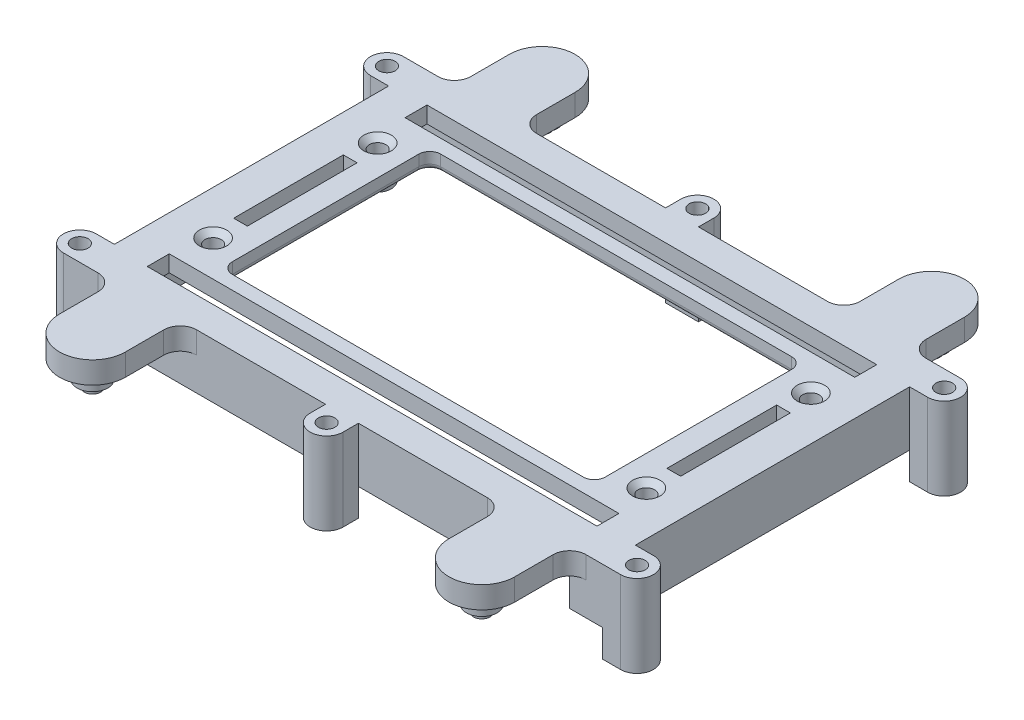
SolidWorks part; units mm, degrees
ref_plane "前视基准面" through (0, 0, 0) normal (0, 0, 1) x (1, 0, 0)
ref_plane "上视基准面" through (0, 0, 0) normal (0, 1, 0) x (1, 0, 0)
ref_plane "右视基准面" through (0, 0, 0) normal (1, 0, 0) x (0, 0, -1)
other "Configuration Table"
sketch "草图1" plane through (0, 0, 0) normal (0, 1, 0) x (1, 0, 0)
  line L0 (0, 35.4779) -> (0, -35.3561) construction
  line L1 (-47.5, 31) -> (-41.5, 31)
  line L2 (-47.5, 25) -> (-47.5, -25)
  line L3 (-47.5, -31) -> (-41.5, -31)
  line L4 (47.5, 25) -> (47.5, -25)
  line L5 (-47.5, 31) -> (47.5, -31) construction
  line L6 (-47.5, -31) -> (47.5, 31) construction
  line L9 (-41.5, 31) -> (-41.5, 41)
  line L11 (-29.5, 31) -> (-29.5, 41)
  line L12 (29.5, 31) -> (29.5, 41)
  line L14 (41.5, 31) -> (41.5, 41)
  line L15 (-78.7463, 0) -> (58.6748, 0) construction
  line L16 (41.5, -31) -> (41.5, -41)
  line L18 (29.5, -31) -> (29.5, -41)
  line L21 (-29.5, -31) -> (-29.5, -41)
  line L23 (-41.5, -31) -> (-41.5, -41)
  line L24 (-29.5, 31) -> (-3, 31)
  line L25 (41.5, 31) -> (47.5, 31)
  line L26 (41.5, -31) -> (47.5, -31)
  line L27 (-29.5, -31) -> (-3, -31)
  line L28 (47.5, 31) -> (50.8, 31)
  line L29 (-47.5, 31) -> (-50.8, 31)
  line L31 (-47.5, 25) -> (-50.8, 25)
  line L33 (47.5, 25) -> (50.8, 25)
  line L36 (47.5, -25) -> (50.8, -25)
  line L37 (47.5, -31) -> (50.8, -31)
  line L38 (-47.5, -31) -> (-50.8, -31)
  line L39 (-47.5, -25) -> (-50.8, -25)
  line L41 (-3, -33.8) -> (-3, -31)
  line L43 (-3, 33.8) -> (-3, 31)
  line L45 (3, 33.8) -> (3, 31)
  line L47 (3, -33.8) -> (3, -31)
  line L48 (3, 31) -> (29.5, 31)
  line L49 (3, -31) -> (29.5, -31)
  arc A0 (-41.5, 41) -> (-29.5, 41) centre (-35.5, 41) cw
  arc A1 (-41.5, -41) -> (-29.5, -41) centre (-35.5, -41) ccw
  arc A2 (41.5, -41) -> (29.5, -41) centre (35.5, -41) cw
  arc A3 (41.5, 41) -> (29.5, 41) centre (35.5, 41) ccw
  arc A4 (-50.8, 31) -> (-50.8, 25) centre (-50.8, 28) ccw
  circle A5 centre (-50.8, 28) radius 1.5
  circle A6 centre (50.8, 28) radius 1.5
  arc A7 (50.8, 31) -> (50.8, 25) centre (50.8, 28) cw
  circle A8 centre (50.8, -28) radius 1.5
  arc A9 (50.8, -31) -> (50.8, -25) centre (50.8, -28) ccw
  circle A10 centre (-50.8, -28) radius 1.5
  arc A11 (-50.8, -31) -> (-50.8, -25) centre (-50.8, -28) cw
  arc A12 (-3, 33.8) -> (3, 33.8) centre (0, 33.8) cw
  circle A13 centre (0, 33.8) radius 1.5
  circle A14 centre (0, -33.8) radius 1.5
  arc A15 (-3, -33.8) -> (3, -33.8) centre (0, -33.8) ccw
  point P0 (0, 0)
  dimension "D8" = 2.8
  dimension "D1" = 95
  dimension "D2" = 62
  dimension "D3" = 83
  dimension "D4" = 12
  dimension "D5" = 10
  dimension "D6" = 3.3
  dimension "D7" = 6
  dimension "D9" = 6
extrude "凸台-拉伸1" add sketch "草图1" against normal blind 15
sketch "草图2" plane through (0, -15, 0) normal (0, -1, 0) x (1, 0, 0)
  line L0 (-63.1336, 0) -> (63.5579, 0) construction
  line L1 (-57.0239, 31) -> (-3, 31)
  line L2 (-57.0239, 31) -> (-57.0239, 48.5806)
  line L3 (-57.0239, 48.5806) -> (57.0239, 48.5806)
  line L4 (57.0239, 31) -> (57.0239, 48.5806)
  line L5 (0, 56.9992) -> (0, -44.1169) construction
  line L6 (3, 33.8) -> (3, 31) construction
  line L7 (-3, 31) -> (-3, 33.8) construction
  line L8 (3, 33.8) -> (3, 31)
  line L9 (-3, 31) -> (-3, 33.8)
  line L10 (3, 31) -> (57.0239, 31)
  line L11 (3, -33.8) -> (3, -31)
  line L12 (-3, -31) -> (-3, -33.8)
  line L13 (-57.0239, -31) -> (-3, -31)
  line L14 (-57.0239, -31) -> (-57.0239, -48.5806)
  line L15 (-57.0239, -48.5806) -> (57.0239, -48.5806)
  line L16 (57.0239, -31) -> (57.0239, -48.5806)
  line L17 (3, -31) -> (57.0239, -31)
  arc A0 (3, 33.8) -> (-3, 33.8) centre (0, 33.8) ccw construction
  arc A1 (3, 33.8) -> (-3, 33.8) centre (0, 33.8) ccw
  arc A2 (3, -33.8) -> (-3, -33.8) centre (0, -33.8) cw
extrude "切除-拉伸1" cut sketch "草图2" against normal blind 11
sketch "草图3" plane through (0, -15, 0) normal (0, -1, 0) x (1, 0, 0)
  line L0 (47.5, 25) -> (47.5, -25) construction
  line L1 (-45, -28.5) -> (45, -28.5)
  line L2 (-45, -28.5) -> (-45, 28.5)
  line L3 (-45, 28.5) -> (45, 28.5)
  line L4 (45, -28.5) -> (45, 28.5)
  line L5 (-45, -28.5) -> (45, 28.5) construction
  line L6 (-45, 28.5) -> (45, -28.5) construction
  line L7 (-50.8, 31) -> (-3, 31) construction
  point P0 (0, 0)
  dimension "D1" = 2.5
  dimension "D2" = 2.5
extrude "切除-拉伸2" cut sketch "草图3" against normal blind 12
sketch "草图4" plane through (0, -4, 0) normal (0, -1, 0) x (1, 0, 0)
  line L0 (-29.5, 41) -> (-41.5, 41) construction
  line L1 (-71.7869, 0) -> (71.1524, 0) construction
  line L2 (0, 61.1393) -> (0, -47.8922) construction
  circle A0 centre (-35.5, 41) radius 2.8
  circle A1 centre (35.5, 41) radius 2.8
  circle A2 centre (35.5, -41) radius 2.8
  circle A3 centre (-35.5, -41) radius 2.8
extrude "凸台-拉伸2" add sketch "草图4" along normal blind 3.3 separate body
sketch "草图5" plane through (0, -7.3, 0) normal (0, -1, 0) x (1, 0, 0)
  line L0 (-58.868, 0) -> (56.1189, 0) construction
  line L1 (0, 46.5823) -> (0, -51.4835) construction
  circle A0 centre (-35.5, 41) radius 1.5
  circle A1 centre (35.5, 41) radius 1.5
  circle A2 centre (35.5, -41) radius 1.5
  circle A3 centre (-35.5, -41) radius 1.5
extrude "凸台-拉伸3" add sketch "草图5" along normal blind 1.3 separate body
sketch "草图6" plane through (0, -15, 0) normal (0, -1, 0) x (1, 0, 0)
  line L0 (-50.8, 31) -> (-3, 31) construction
  line L1 (-47.5, 31) -> (47.5, 31)
  line L2 (-47.5, 31) -> (-47.5, -31)
  line L3 (-47.5, -31) -> (47.5, -31)
  line L4 (47.5, 31) -> (47.5, -31)
  line L5 (50.8, -31) -> (3, -31) construction
extrude "切除-拉伸3" cut sketch "草图6" against normal blind 5
sketch "草图7" plane through (0, -3, 0) normal (0, -1, 0) x (1, 0, 0)
  line L0 (-60.2485, 0) -> (64.067, 0) construction
  line L1 (0, 41.3678) -> (0, -47.8169) construction
  line L2 (-30, -23) -> (30, -23)
  line L3 (-30, 25) -> (-2, 25)
  line L4 (-30, 25) -> (-30, 23)
  line L5 (-30, 23) -> (30, 23)
  line L6 (30, 25) -> (30, 23)
  line L7 (-30, 25) -> (30, 23) construction
  line L8 (-30, 23) -> (30, 25) construction
  line L9 (30, -25) -> (30, -23)
  line L10 (-30, -25) -> (-2, -25)
  line L11 (-30, -25) -> (-30, -23)
  line L12 (45, 28.5) -> (-45, 28.5) construction
  line L13 (-2, 28.5) -> (2, 28.5)
  line L14 (-2, 28.5) -> (-2, 25)
  line L16 (2, 28.5) -> (2, 25)
  line L18 (2, -28.5) -> (2, -25)
  line L19 (-2, -28.5) -> (2, -28.5)
  line L20 (-2, -28.5) -> (-2, -25)
  line L21 (2, 25) -> (30, 25)
  line L22 (2, -25) -> (30, -25)
  line L23 (-45, -28.5) -> (-45, 28.5) construction
  line L24 (-42, 10) -> (-40, 10)
  line L25 (-42, 10) -> (-42, 2)
  line L26 (-42, -10) -> (-40, -10)
  line L27 (-40, 10) -> (-40, -10)
  line L28 (-42, 10) -> (-40, -10) construction
  line L29 (-42, -10) -> (-40, 10) construction
  line L30 (-42, -2) -> (-42, -10)
  line L31 (-45, 2) -> (-42, 2)
  line L32 (-45, 2) -> (-45, -2)
  line L33 (-45, -2) -> (-42, -2)
  line L35 (45, -2) -> (42, -2)
  line L36 (45, 2) -> (45, -2)
  line L37 (45, 2) -> (42, 2)
  line L38 (42, 10) -> (42, 2)
  line L39 (42, 10) -> (40, 10)
  line L40 (40, 10) -> (40, -10)
  line L41 (42, -10) -> (40, -10)
  line L42 (42, -2) -> (42, -10)
  point P5 (0, 24)
  point P24 (-41, 0)
  dimension "D1" = 23
  dimension "D2" = 2
  dimension "D3" = 60
  dimension "D4" = 4
  dimension "D5" = 2
  dimension "D6" = 20
  dimension "D7" = 3
  dimension "D8" = 4
extrude "凸台-拉伸4" [suppressed] add sketch "草图7" along normal blind 2.5
sketch "草图9" plane through (0, -10, 0) normal (0, -1, 0) x (1, 0, 0)
  line L0 (-45, 28.5) -> (45, 28.5) construction
  line L1 (41.5, 31) -> (32, 31)
  line L2 (41.5, 31) -> (41.5, 28.5)
  line L3 (41.5, 28.5) -> (32, 28.5)
  line L4 (32, 31) -> (32, 28.5)
  dimension "D1" = 9.5
extrude "切除-拉伸4" cut sketch "草图9" against normal blind 5
sketch "草图10" plane through (0, 0, 0) normal (0, 1, 0) x (1, 0, 0)
  line L1 (-32, -19) -> (32, -19)
  line L2 (-34, -17) -> (-34, 17)
  line L3 (-32, 19) -> (32, 19)
  line L4 (34, -17) -> (34, 17)
  line L5 (-34, -19) -> (34, 19) construction
  line L6 (-34, 19) -> (34, -19) construction
  arc A0 (-32, -19) -> (-34, -17) centre (-32, -17) cw
  arc A1 (32, -19) -> (34, -17) centre (32, -17) ccw
  arc A2 (32, 19) -> (34, 17) centre (32, 17) cw
  arc A3 (-34, 17) -> (-32, 19) centre (-32, 17) cw
  point P0 (0, 0)
  dimension "D3" = 2
  dimension "D1" = 68
  dimension "D2" = 38
extrude "切除-拉伸5" cut sketch "草图10" against normal through all
fillet "圆角1" radius 3 8 edges at (41.5, -2, 31) (29.5, -2, 31) (-29.5, -2, 31) (-41.5, -2, 31) (-41.5, -2, -31) (-29.5, -2, -31) (29.5, -2, -31) (41.5, -2, -31)
fillet "圆角3" radius 1 12 edges at (0, -3, -28.5) (-45, -3, 0) (0, -3, 28.5) (45, -3, 0) (-33.4142, -3, -18.4142) (0, -3, -19) (33.4142, -3, -18.4142) (34, -3, 0) (33.4142, -3, 18.4142) (0, -3, 19) (-33.4142, -3, 18.4142) (-34, -3, 0)
combine bodies "组合1" operation type add bodies to combine 111 121 115 109 112 113 116 110 121 121 114
fillet "圆角4" [suppressed] radius 1
sketch "草图12" plane through (0, -3, 0) normal (0, -1, 0) x (1, 0, 0)
  line L0 (-57.3633, 0) -> (63.3882, 0) construction
  line L1 (-45, -28.5) -> (-45, 28.5) construction
  line L2 (0, 45.8091) -> (0, -49.9604) construction
  circle A0 centre (-39.5, 15) radius 2.5
  circle A1 centre (-39.5, -15) radius 2.5
  circle A2 centre (39.5, -15) radius 2.5
  circle A3 centre (39.5, 15) radius 2.5
  dimension "D1" = 5.5
  dimension "D2" = 15
extrude "凸台-拉伸5" add sketch "草图12" along normal blind 3
sketch "草图13" plane through (0, -6, 0) normal (0, -1, 0) x (1, 0, 0)
  circle A0 centre (-39.5, 15) radius 1.5
  circle A1 centre (39.5, 15) radius 2.5
  circle A2 centre (39.5, 15) radius 2.5
  circle A3 centre (39.5, -15) radius 2.5
  circle A4 centre (39.5, -15) radius 2.5
  circle A5 centre (-39.5, -15) radius 2.5
  circle A6 centre (-39.5, -15) radius 2.5
  circle A7 centre (-39.5, 15) radius 2.5
  circle A8 centre (-39.5, 15) radius 2.5
  circle A9 centre (39.5, 15) radius 1.5
  circle A10 centre (39.5, -15) radius 1.5
  circle A11 centre (-39.5, -15) radius 1.5
  dimension "D1" = 0
  dimension "D2" = 0
  dimension "D3" = 0
  dimension "D4" = 0
  dimension "D5" = 1
extrude "切除-拉伸6" cut sketch "草图13" against normal through all contours A10 | A9 | A11 | A0
chamfer "倒角1" distance 1 angle 45 4 edges at (-39.5, 0, 13.5) (39.5, 0, 13.5) (39.5, 0, -16.5) (-39.5, 0, -16.5)
sketch "草图14" plane through (0, -3, 0) normal (0, -1, 0) x (1, 0, 0)
  line L0 (8.25, 0) -> (-8.25, 0) construction
  line L1 (-42, 24) -> (-37, 24)
  line L2 (-42, 24) -> (-42, 20)
  line L3 (-42, 20) -> (-37, 20)
  line L4 (-37, 24) -> (-37, 20)
  line L5 (-42, 24) -> (-37, 20) construction
  line L6 (-42, 20) -> (-37, 24) construction
  line L7 (-42, -20) -> (-37, -20)
  line L8 (-37, -24) -> (-37, -20)
  line L9 (-42, -24) -> (-37, -24)
  line L10 (-42, -24) -> (-42, -20)
  line L11 (0, -8.25) -> (0, 8.25) construction
  line L12 (42, -24) -> (42, -20)
  line L13 (42, -24) -> (37, -24)
  line L14 (37, -24) -> (37, -20)
  line L15 (42, -20) -> (37, -20)
  line L16 (42, 20) -> (37, 20)
  line L17 (37, 24) -> (37, 20)
  line L18 (42, 24) -> (37, 24)
  line L19 (42, 24) -> (42, 20)
  point P0 (-39.5, 22)
  dimension "D1" = 22
  dimension "D2" = 5
  dimension "D3" = 4
extrude "切除-拉伸7" [suppressed] cut sketch "草图14" against normal through all
sketch "草图15" plane through (0, -3, 0) normal (0, -1, 0) x (1, 0, 0)
  line L0 (-45, 28.5) -> (32, 28.5) construction
  line L1 (-41, 25.5) -> (41, 25.5)
  line L2 (-41, 25.5) -> (-41, 21.5)
  line L3 (-41, 21.5) -> (41, 21.5)
  line L4 (41, 25.5) -> (41, 21.5)
  line L5 (-41, 25.5) -> (41, 21.5) construction
  line L6 (-41, 21.5) -> (41, 25.5) construction
  line L7 (8.25, 0) -> (-8.25, 0) construction
  line L8 (-41, -21.5) -> (41, -21.5)
  line L9 (41, -25.5) -> (41, -21.5)
  line L10 (-41, -25.5) -> (41, -25.5)
  line L11 (-41, -25.5) -> (-41, -21.5)
  line L12 (0, -8.25) -> (0, 8.25) construction
  line L13 (-40.75, 10) -> (-38.25, 10)
  line L14 (-40.75, 10) -> (-40.75, -10)
  line L15 (-40.75, -10) -> (-38.25, -10)
  line L16 (-38.25, 10) -> (-38.25, -10)
  line L17 (-40.75, 10) -> (-38.25, -10) construction
  line L18 (-40.75, -10) -> (-38.25, 10) construction
  line L19 (40.75, -10) -> (38.25, -10)
  line L20 (38.25, 10) -> (38.25, -10)
  line L21 (40.75, 10) -> (38.25, 10)
  line L22 (40.75, 10) -> (40.75, -10)
  point P0 (0, 23.5)
  point P5 (-39.5, 0)
  point P18 (0, 0)
  dimension "D1" = 4
  dimension "D2" = 5
  dimension "D3" = 82
  dimension "D4" = 2.5
  dimension "D5" = 20
extrude "切除-拉伸8" cut sketch "草图15" against normal through all
